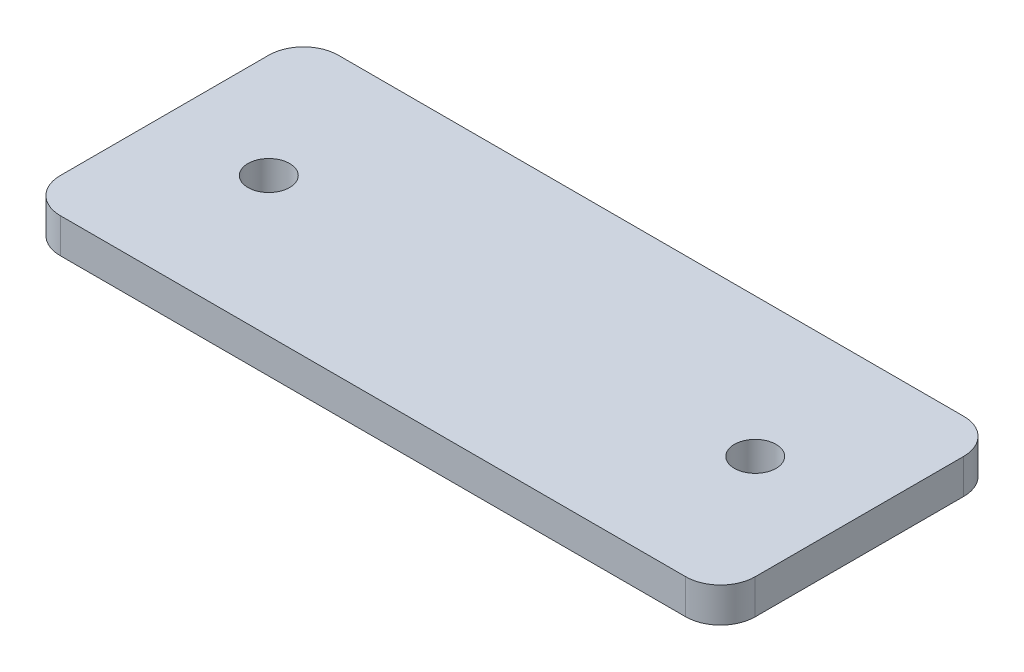
SolidWorks part; units mm, degrees
ref_plane "Plano frontal" through (0, 0, 0) normal (0, 0, 1) x (1, 0, 0)
ref_plane "Plano superior" through (0, 0, 0) normal (0, 1, 0) x (1, 0, 0)
ref_plane "Plano direito" through (0, 0, 0) normal (1, 0, 0) x (0, 0, -1)
sketch "Esboço1" plane through (0, 0, 0) normal (0, 1, 0) x (1, 0, 0)
  line L1 (50, -20) -> (-50, -20)
  line L2 (50, -20) -> (50, 20)
  line L3 (50, 20) -> (-50, 20)
  line L4 (-50, -20) -> (-50, 20)
  line L5 (50, -20) -> (-50, 20) construction
  line L6 (50, 20) -> (-50, -20) construction
  point P0 (0, 0)
  dimension "D1" = 40
  dimension "D2" = 100
extrude "Ressalto-extrusão1" add sketch "Esboço1" along normal blind 5
fillet "Filete1" radius 5 4 edges at (-50, 2.5, -20) (-50, 2.5, 20) (50, 2.5, -20) (50, 2.5, 20)
sketch "Esboço2" plane through (0, 5, 0) normal (0, 1, 0) x (1, 0, 0)
  line L0 (-50, 0) -> (50, 0) construction
  line L1 (-50, 15) -> (-50, -15) construction
  line L2 (50, -15) -> (50, 15) construction
  circle A0 centre (-35, 0) radius 3
  circle A1 centre (35, 0) radius 3
  dimension "D1" = 6
  dimension "D2" = 15
  dimension "D3" = 15
extrude "Corte-extrusão1" cut sketch "Esboço2" against normal blind 5
